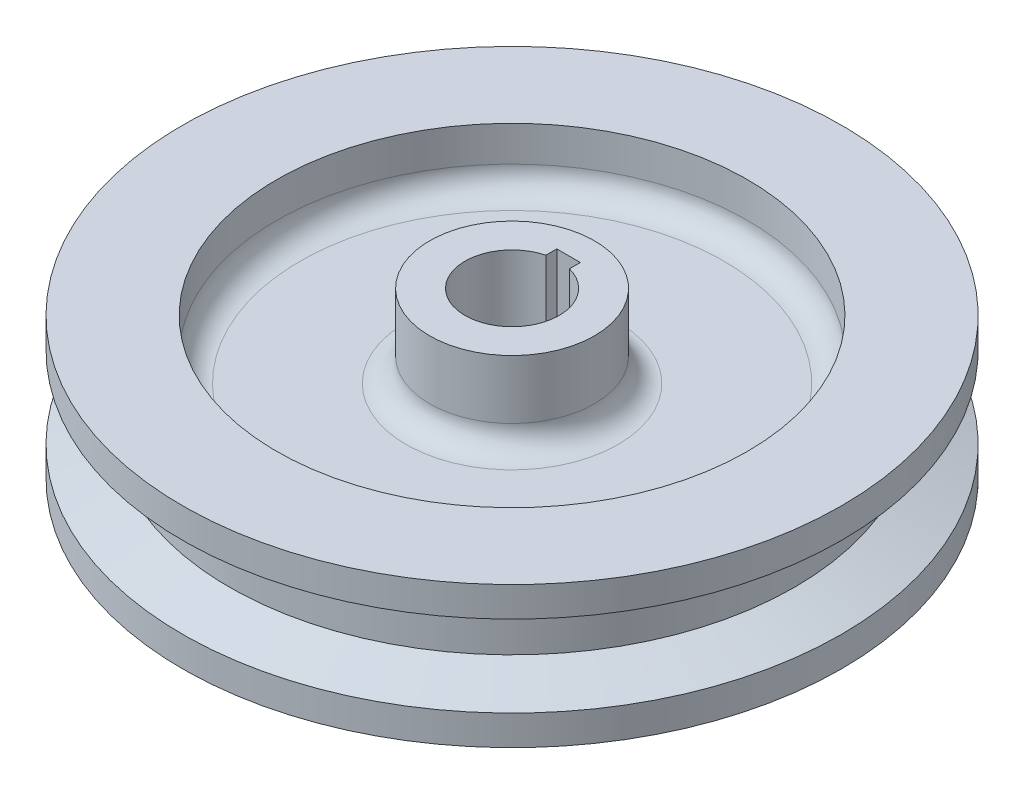
SolidWorks part; units mm, degrees
ref_plane "Front Plane" through (0, 0, 0) normal (0, 0, 1) x (1, 0, 0)
ref_plane "Top Plane" through (0, 0, 0) normal (0, 1, 0) x (1, 0, 0)
ref_plane "Right Plane" through (0, 0, 0) normal (1, 0, 0) x (0, 0, -1)
sketch "Sketch1" plane through (0, 0, 0) normal (0, 0, 1) x (1, 0, 0)
  line L0 (0, -1000) -> (0, 49000) construction
  line L1 (-1000, 0) -> (49000, 0) construction
  line L2 (12.7, 25.4) -> (22.225, 25.4)
  line L3 (22.225, 25.4) -> (22.225, 9.525)
  line L4 (28.575, 3.175) -> (57.15, 3.175)
  line L5 (63.5, 9.525) -> (63.5, 19.05)
  line L6 (63.5, 19.05) -> (88.9, 19.05)
  line L7 (88.9, 19.05) -> (88.9, 10.9724)
  line L8 (88.9, 10.9724) -> (76.2, 6.35)
  line L9 (76.2, 6.35) -> (76.2, -6.35)
  line L10 (88.9, -10.9724) -> (76.2, -6.35)
  line L11 (88.9, -19.05) -> (88.9, -10.9724)
  line L12 (63.5, -19.05) -> (88.9, -19.05)
  line L13 (63.5, -9.525) -> (63.5, -19.05)
  line L14 (28.575, -3.175) -> (57.15, -3.175)
  line L15 (22.225, -25.4) -> (22.225, -9.525)
  line L16 (12.7, -25.4) -> (22.225, -25.4)
  line L17 (12.7, 25.4) -> (12.7, -25.4)
  arc A0 (63.5, 9.525) -> (57.15, 3.175) centre (57.15, 9.525) cw
  arc A1 (28.575, 3.175) -> (22.225, 9.525) centre (28.575, 9.525) cw
  arc A2 (28.575, -3.175) -> (22.225, -9.525) centre (28.575, -9.525) ccw
  arc A3 (63.5, -9.525) -> (57.15, -3.175) centre (57.15, -9.525) ccw
  point P4 (0, 0)
  point P27 (76.2, 0)
  dimension "D9" = 6.35
  dimension "D1" = 177.8
  dimension "D2" = 44.45
  dimension "D3" = 6.35
  dimension "D4" = 38.1
  dimension "D5" = 50.8
  dimension "D6" = 6.35
  dimension "D7" = 12.7
  dimension "D8" = 20
  dimension "D10" = 127
  dimension "D11" = 25.4
revolve "Revolve1" add sketch "Sketch1" angle 360 about L0
sketch "Sketch2" plane through (0, 25.4, 0) normal (0, 1, 0) x (1, 0, 0)
  line L0 (-201000, 0) -> (249000, 0) construction
  line L1 (3.175, 0) -> (-3.175, 0)
  line L2 (3.175, 0) -> (3.175, 15.24)
  line L3 (3.175, 15.24) -> (-3.175, 15.24)
  line L4 (-3.175, 0) -> (-3.175, 15.24)
  line L5 (3.175, 0) -> (-3.175, 15.24) construction
  line L6 (3.175, 15.24) -> (-3.175, 0) construction
  line L7 (-201000, 0) -> (249000, 0) construction
  point P0 (0, 7.62)
  dimension "D1" = 15.24
  dimension "D2" = 6.35
extrude "Cut-Extrude1" cut sketch "Sketch2" against normal up to surface (50.8 mm away) up to face at (22.225, -25.4, 0)
